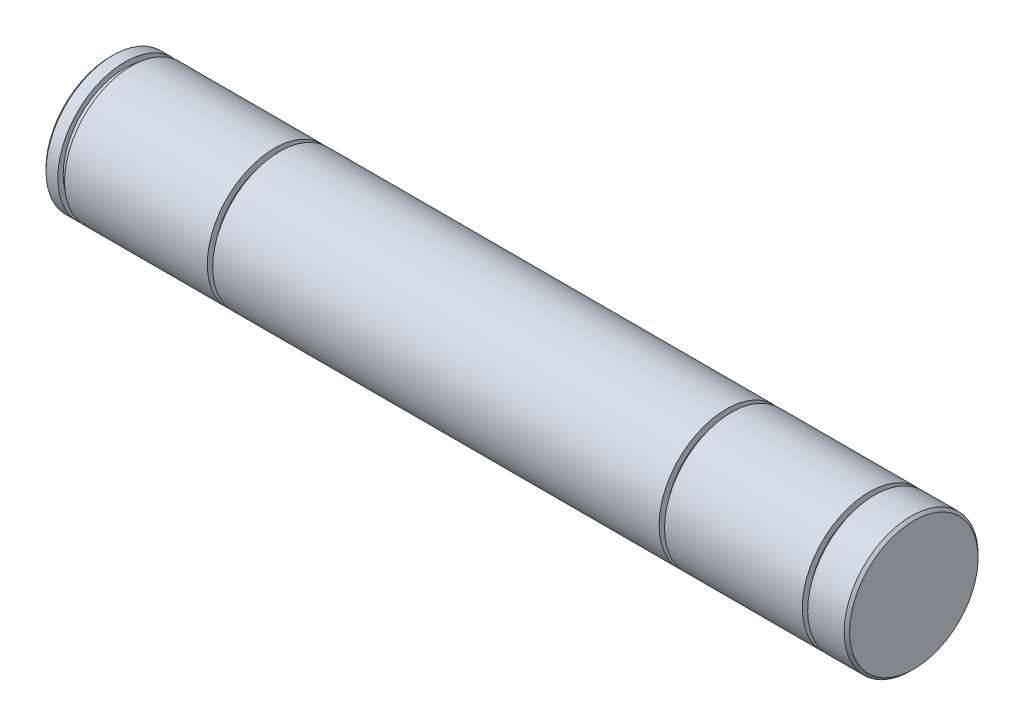
SolidWorks part; units mm, degrees
ref_plane "Plano frontal" through (0, 0, 0) normal (0, 0, 1) x (1, 0, 0)
ref_plane "Plano superior" through (0, 0, 0) normal (0, 1, 0) x (1, 0, 0)
ref_plane "Plano direito" through (0, 0, 0) normal (1, 0, 0) x (0, 0, -1)
sketch "Esboço1" plane through (0, 0, 0) normal (0, 0, 1) x (1, 0, 0)
  line L0 (0, 0) -> (300, 0)
  line L1 (0, 0) -> (0, 24)
  line L2 (1, 25) -> (5.4146, 25)
  line L7 (5.4146, 25) -> (5.4146, 23)
  line L8 (5.4146, 23) -> (7.9146, 23)
  line L9 (7.9146, 23) -> (7.9146, 25)
  line L16 (220, 25) -> (229.9101, 25)
  line L17 (300, 24) -> (300, 0)
  line L18 (7.9146, 25) -> (61.2199, 25)
  line L19 (61.2199, 25) -> (61.2199, 22.5)
  line L20 (61.2199, 22.5) -> (63.2199, 22.5)
  line L21 (63.2199, 22.5) -> (63.2199, 25)
  line L22 (63.2199, 25) -> (220, 25)
  line L23 (229.9101, 25) -> (229.9101, 22.5)
  line L24 (229.9101, 22.5) -> (231.9101, 22.5)
  line L25 (231.9101, 22.5) -> (231.9101, 25)
  line L26 (231.9101, 25) -> (283.3633, 25)
  line L27 (283.3633, 25) -> (283.3633, 22.5)
  line L28 (283.3633, 22.5) -> (285.3633, 22.5)
  line L29 (285.3633, 22.5) -> (285.3633, 25)
  line L30 (285.3633, 25) -> (299, 25)
  line L32 (0, 24) -> (1, 25)
  line L33 (299, 25) -> (300, 24)
  point P1 (0, 0)
  point P4 (0, 25)
  point P5 (0, 0)
  point P19 (300, 25)
  dimension "D1" = 25
  dimension "D6" = 2.5
  dimension "D7" = 2
  dimension "D8" = 2
  dimension "D9" = 2.5
  dimension "D10" = 80
  dimension "D11" = 2.5
  dimension "D12" = 2
  dimension "D13" = 2.5
  dimension "D14" = 2
revolve "Revolução1" add sketch "Esboço1" angle 360 about L0
